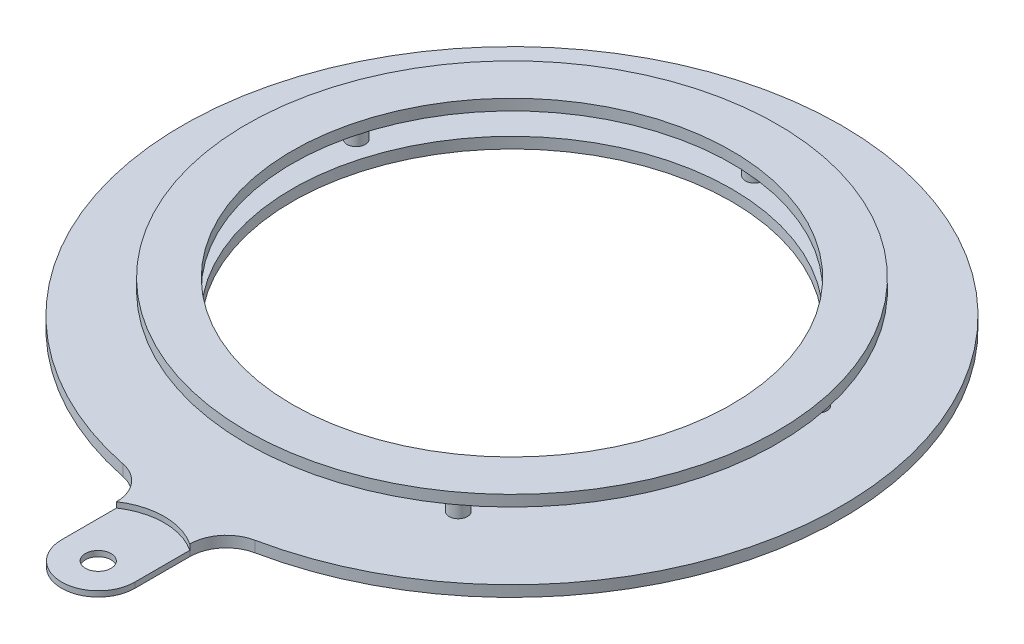
SolidWorks part; units mm, degrees
ref_plane "前视基准面" through (0, 0, 0) normal (0, 0, 1) x (1, 0, 0)
ref_plane "上视基准面" through (0, 0, 0) normal (0, 1, 0) x (1, 0, 0)
ref_plane "右视基准面" through (0, 0, 0) normal (1, 0, 0) x (0, 0, -1)
sketch "草图1" plane through (0, 0, 0) normal (0, 1, 0) x (1, 0, 0)
  circle A0 centre (0, 0) radius 72.5
  circle A1 centre (0, 0) radius 60
  dimension "D1" = 145
  dimension "D2" = 120
extrude "凸台-拉伸1" add sketch "草图1" along normal blind 3
sketch "草图2" plane through (0, 0, 0) normal (0, 1, 0) x (1, 0, 0)
  line L0 (0, 72.5) -> (0, 60) construction
  circle A0 centre (0, 0) radius 72.5 construction
  circle A1 centre (0, 0) radius 60 construction
  circle A2 centre (0, 66.25) radius 2.5
  dimension "D1" = 5
extrude "凸台-拉伸2" add sketch "草图2" against normal blind 6
pattern_circular "阵列(圆周)1" count 5 over 360 about axis through (0, 0, 0) along (0, 1, 0) of "凸台-拉伸2"
sketch "草图3" plane through (0, -6, 0) normal (0, -1, 0) x (1, 0, 0)
  line L0 (0, -41.49) -> (0, 174.9176) construction
  line L1 (10, 112.9796) -> (10, 97.9796)
  line L2 (-10, 112.9796) -> (-10, 97.9796)
  arc A1 (-10, 97.9796) -> (-18, 88.1816) centre (-20, 97.9796) cw
  circle A3 centre (0, 0) radius 60 construction
  circle A4 centre (0, 0) radius 60
  arc A5 (-18, 88.1816) -> (18, 88.1816) centre (0, 0) ccw
  arc A6 (10, 112.9796) -> (-10, 112.9796) centre (0, 112.9796) ccw
  arc A7 (10, 97.9796) -> (18, 88.1816) centre (20, 97.9796) ccw
  dimension "D1" = 180
  dimension "D2" = 20
  dimension "D3" = 10
  dimension "D4" = 15
extrude "凸台-拉伸3" add sketch "草图3" along normal blind 3
sketch "草图4" plane through (0, 0, 0) normal (0, 1, 0) x (1, 0, 0)
  circle A0 centre (0, -112.9796) radius 3.5
  dimension "D1" = 7
extrude "切除-拉伸1" cut sketch "草图4" against normal blind 10
sketch "草图5" plane through (0, -6, 0) normal (0, 1, 0) x (1, 0, 0)
  circle A0 centre (0, -112.9796) radius 18.0278
extrude "切除-拉伸2" cut sketch "草图5" against normal blind 1.5
